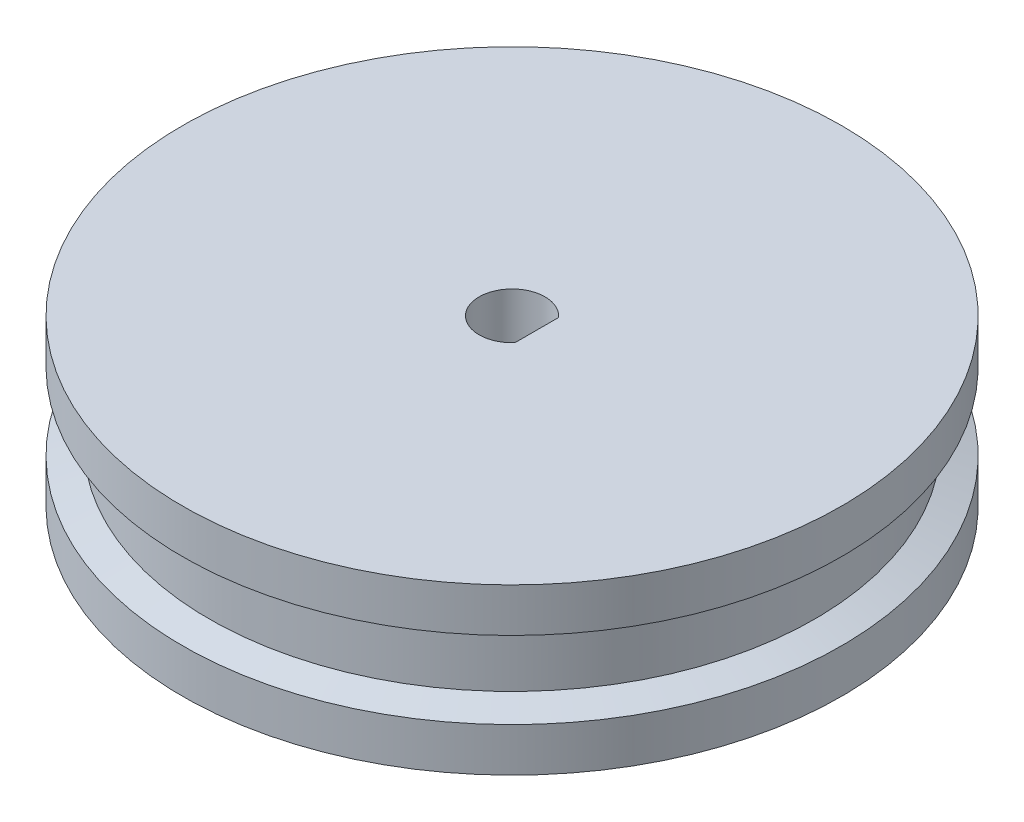
SolidWorks part; units mm, degrees
material "Aleación 1060"
ref_plane "Alzado" through (0, 0, 0) normal (0, 0, 1) x (1, 0, 0)
ref_plane "Planta" through (0, 0, 0) normal (0, 1, 0) x (1, 0, 0)
ref_plane "Vista lateral" through (0, 0, 0) normal (1, 0, 0) x (0, 0, -1)
sketch "Croquis1" plane through (0, 0, 0) normal (1, 0, 0) x (0, 0, -1)
  line L0 (40, 10) -> (0, 10)
  line L1 (0, 0) -> (0, 14.768) construction
  line L4 (40, -10) -> (40, -4.6829)
  line L5 (40, -4.6829) -> (36.75, -3.5)
  line L6 (36.75, -3.5) -> (36.75, 3.5)
  line L7 (36.75, 3.5) -> (40, 4.6829)
  line L9 (40, 10) -> (40, 4.6829)
  line L10 (0, 10) -> (0, -10)
  line L11 (0, -10) -> (40, -10)
  line L12 (0, 0) -> (36.75, 0) construction
  dimension "D1" = 20
  dimension "D2" = 10
  dimension "D3" = 10
  dimension "D4" = 36.75
  dimension "D5" = 7
  dimension "D6" = 40
  dimension "D7" = 40
  dimension "D8" = 20
revolve "Revolución1" add sketch "Croquis1" angle 360 about L1
sketch "Croquis2" plane through (0, 0, 0) normal (0, 1, 0) x (1, 0, 0)
  line L0 (-4, 0) -> (3, 0) construction
  line L1 (3, 2.6458) -> (3, -2.6458)
  arc A0 (3, 2.6458) -> (3, -2.6458) centre (0, 0) ccw
  point P8 (3, 0)
  dimension "D1" = 8
  dimension "D2" = 7
extrude "Cortar-Extruir1" cut sketch "Croquis2" against normal mid plane 30
